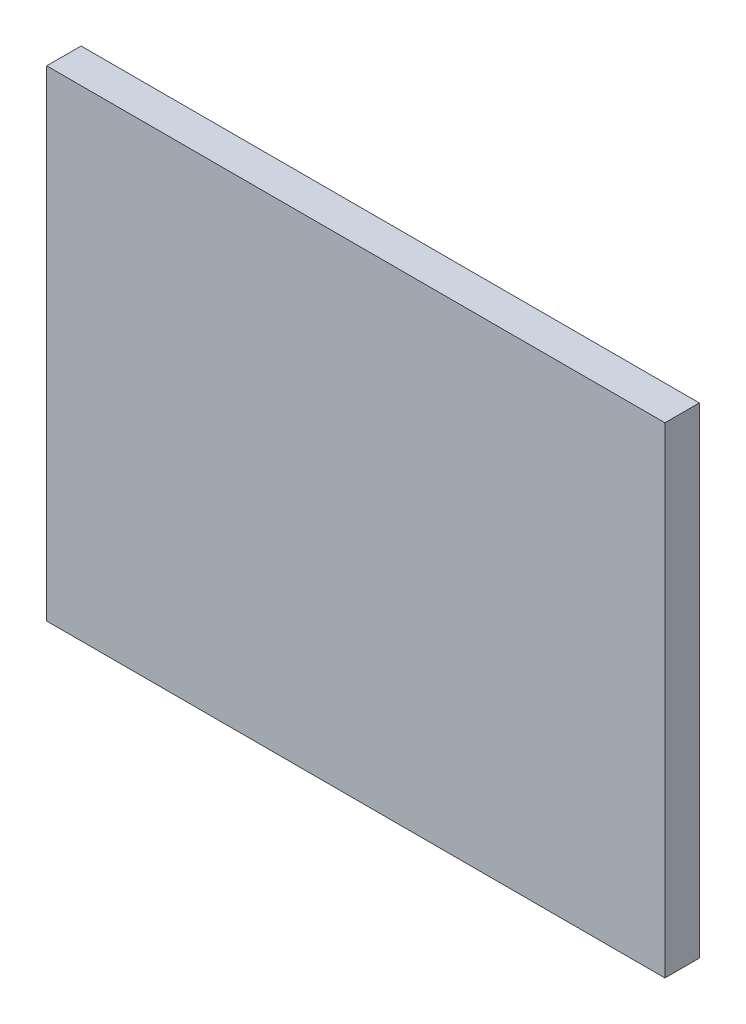
SolidWorks part; units mm, degrees
ref_plane "Front Plane" through (0, 0, 0) normal (0, 0, 1) x (1, 0, 0)
ref_plane "Top Plane" through (0, 0, 0) normal (0, 1, 0) x (1, 0, 0)
ref_plane "Right Plane" through (0, 0, 0) normal (1, 0, 0) x (0, 0, -1)
sketch "Sketch1" plane through (0, 0, 0) normal (0, 0, 1) x (1, 0, 0)
  line L1 (45, -35) -> (-45, -35)
  line L2 (45, -35) -> (45, 35)
  line L3 (45, 35) -> (-45, 35)
  line L4 (-45, -35) -> (-45, 35)
  line L5 (45, -35) -> (-45, 35) construction
  line L6 (45, 35) -> (-45, -35) construction
  point P0 (0, 0)
  dimension "D1" = 90
  dimension "D2" = 70
extrude "Boss-Extrude1" add sketch "Sketch1" along normal blind 5
